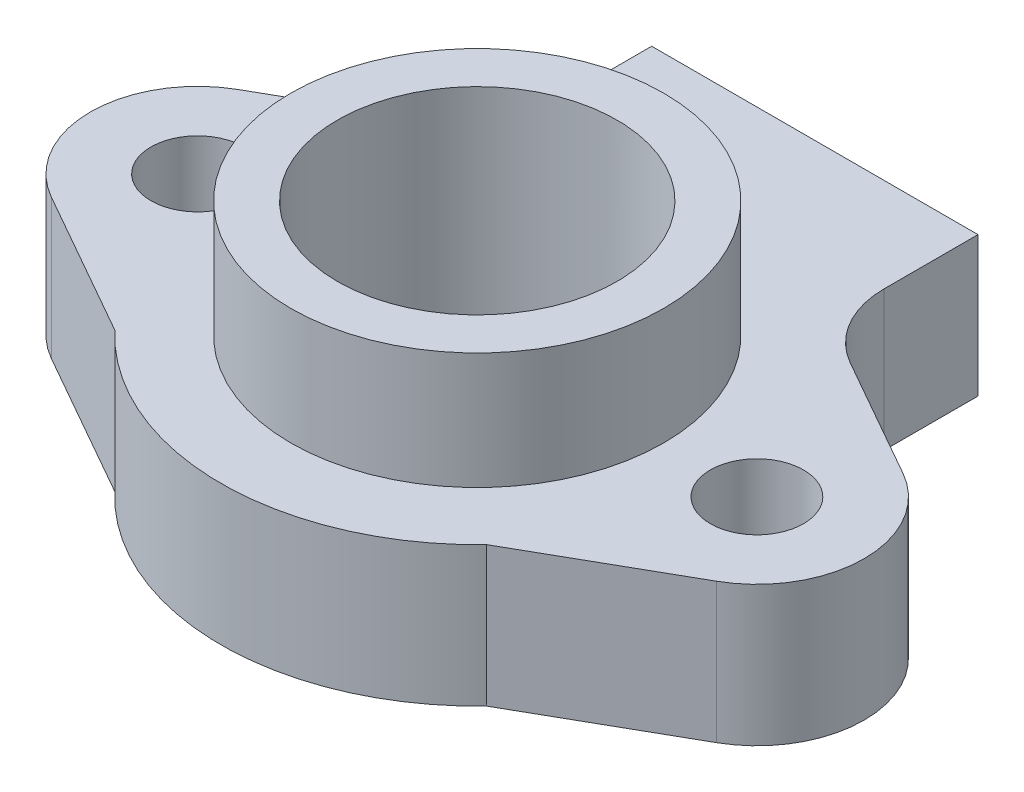
SolidWorks part; units mm, degrees
ref_plane "Front Plane" through (0, 0, 0) normal (0, 0, 1) x (1, 0, 0)
ref_plane "Top Plane" through (0, 0, 0) normal (0, 1, 0) x (1, 0, 0)
ref_plane "Right Plane" through (0, 0, 0) normal (1, 0, 0) x (0, 0, -1)
sketch "Sketch1" plane through (0, 0, 0) normal (0, 1, 0) x (1, 0, 0)
  circle A0 centre (0, 0) radius 30
  circle A1 centre (0, 0) radius 40
  dimension "D1" = 80
  dimension "D2" = 60
extrude "Boss-Extrude1" add sketch "Sketch1" along normal blind 55 and the other way blind 5
sketch "Sketch2" plane through (0, 0, 0) normal (0, 1, 0) x (1, 0, 0)
  line L0 (71.359, -19.9993) -> (39.875, -37.8812)
  line L1 (-71.359, -19.9993) -> (-39.875, -37.8812)
  line L2 (-60, 0) -> (60, 0) construction
  line L3 (71.359, 19.9993) -> (39.875, 37.8812)
  line L4 (-71.359, 19.9993) -> (-39.875, 37.8812)
  line L5 (-35, 72.4264) -> (-35, 40.65)
  line L6 (0, 0) -> (0, -55) construction
  line L7 (35, 72.4264) -> (35, 40.65)
  line L8 (-35, 72.4264) -> (35, 72.4264)
  line L9 (-39.875, 37.8812) -> (-35, 40.65)
  line L10 (39.875, 37.8812) -> (35, 40.65)
  arc A0 (-71.359, 19.9993) -> (-71.359, -19.9993) centre (-60, 0) ccw
  arc A1 (71.359, -19.9993) -> (71.359, 19.9993) centre (60, 0) ccw
  arc A3 (39.875, -37.8812) -> (-39.875, -37.8812) centre (0, 0) cw
  circle A5 centre (-60, 0) radius 10
  circle A6 centre (60, 0) radius 10
  circle A7 centre (0, 0) radius 30 construction
  circle A8 centre (0, 0) radius 30
  dimension "D3" = 55
  dimension "D4" = 46
  dimension "D7" = 20
  dimension "D1" = 120
  dimension "D2" = 60
  dimension "D5" = 35
extrude "Boss-Extrude2" add sketch "Sketch2" along normal blind 30
fillet "Fillet1" radius 20 2 edges at (-35, 15, -40.65) (35, 15, -40.65)
sketch "Sketch3" plane through (0, 0, -72.4264) normal (0, 0, -1) x (-1, 0, 0)
  line L0 (35, 15) -> (-35, 15) construction
  line L1 (35, 30) -> (35, 0) construction
  line L2 (-35, 30) -> (-35, 0) construction
  line L4 (30, 25) -> (-30, 25)
  line L5 (30, 25) -> (30, 5)
  line L6 (30, 5) -> (-30, 5)
  line L7 (-30, 25) -> (-30, 5)
  line L8 (30, 25) -> (-30, 5) construction
  line L9 (30, 5) -> (-30, 25) construction
  point P6 (0, 15)
  dimension "D1" = 20
  dimension "D2" = 5
extrude "Cut-Extrude1" cut sketch "Sketch3" against normal blind 25
sketch "Sketch4" plane through (0, 0, -47.4264) normal (0, 0, -1) x (-1, 0, 0)
  line L0 (-30, 15) -> (30, 15) construction
  line L1 (-30, 25) -> (-30, 5) construction
  line L2 (30, 5) -> (30, 25) construction
  point P6 (0, 15)
hole_wizard "M10x1.0 Tapped Hole1" positions "3DSketch1" profile "Sketch5" tap size "M10x1.0" standard "ISO"
sketch3d "3DSketch1"
  point P0 (0, 15, -47.4264)
sketch "Sketch5" plane through (0, 15, -47.4264) normal (1, 0, 0) x (0, 1, 0)
  line L0 (0, 0) -> (0, 45.7039)
  line L1 (0, 45.7039) -> (4.5, 43)
  line L2 (4.5, 43) -> (4.5, 0)
  line L5 (4.5, 0) -> (0, 0)
  line L10 (0, 45.7039) -> (-4.5, 43) construction
  line L11 (0, -6.35) -> (0, 107.95) construction
  dimension "Tap Drill Dia." = 9
  dimension "Tap Drill Depth" = 43
  dimension "Drill Angle" = 118
